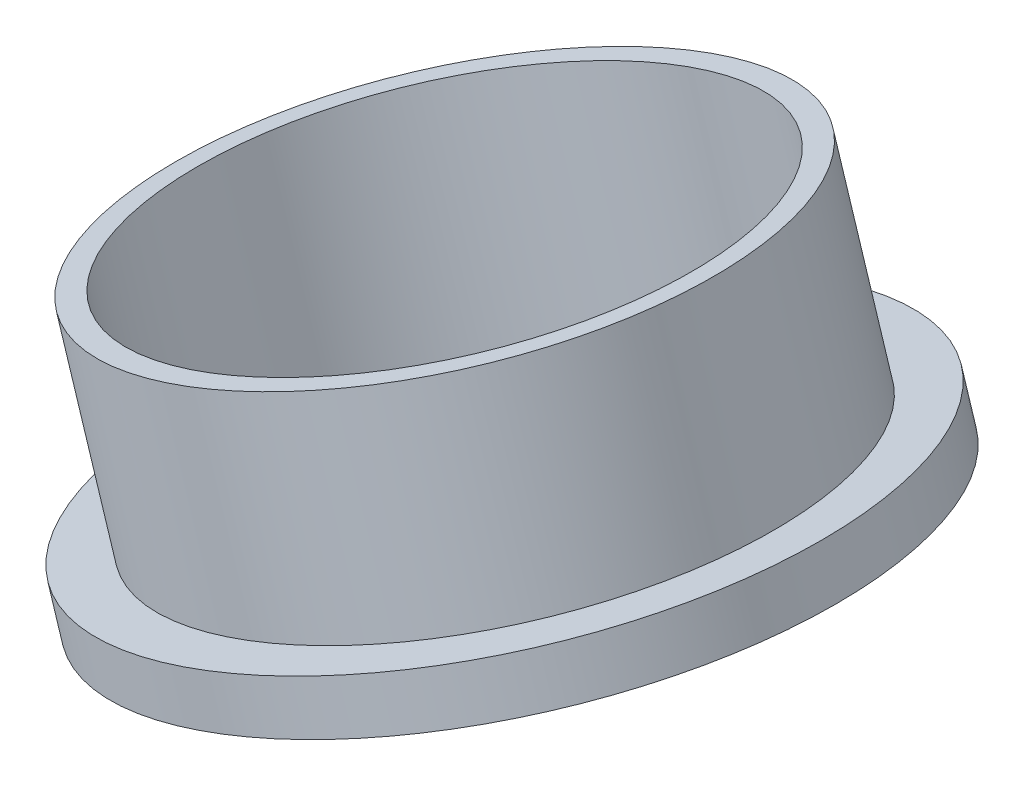
SolidWorks part; units mm, degrees
material "6061-T6 (SS)"
ref_plane "Alzado" through (0, 0, 0) normal (0, 0, 1) x (1, 0, 0)
ref_plane "Planta" through (0, 0, 0) normal (0, 1, 0) x (1, 0, 0)
ref_plane "Vista lateral" through (0, 0, 0) normal (1, 0, 0) x (0, 0, -1)
sketch "Sk_Cazoleta" plane through (0, 0, 0) normal (0, 0, 1) x (1, 0, 0)
  line L0 (420.6694, 409.5157) -> (422.0046, 409.9367)
  line L1 (422.0046, 409.9367) -> (425.6131, 398.4921)
  line L2 (425.6131, 398.4921) -> (428.4743, 399.3943)
  line L3 (428.4743, 399.3943) -> (429.3764, 396.5331)
  line L4 (429.3764, 396.5331) -> (425.1801, 395.21)
  line L5 (425.1801, 395.21) -> (420.6694, 409.5157)
  line L6 (404.2879, 409.5931) -> (414.8129, 376.2131) construction
revolve "Cazoleta" add sketch "Sk_Cazoleta" angle 360 about L6
